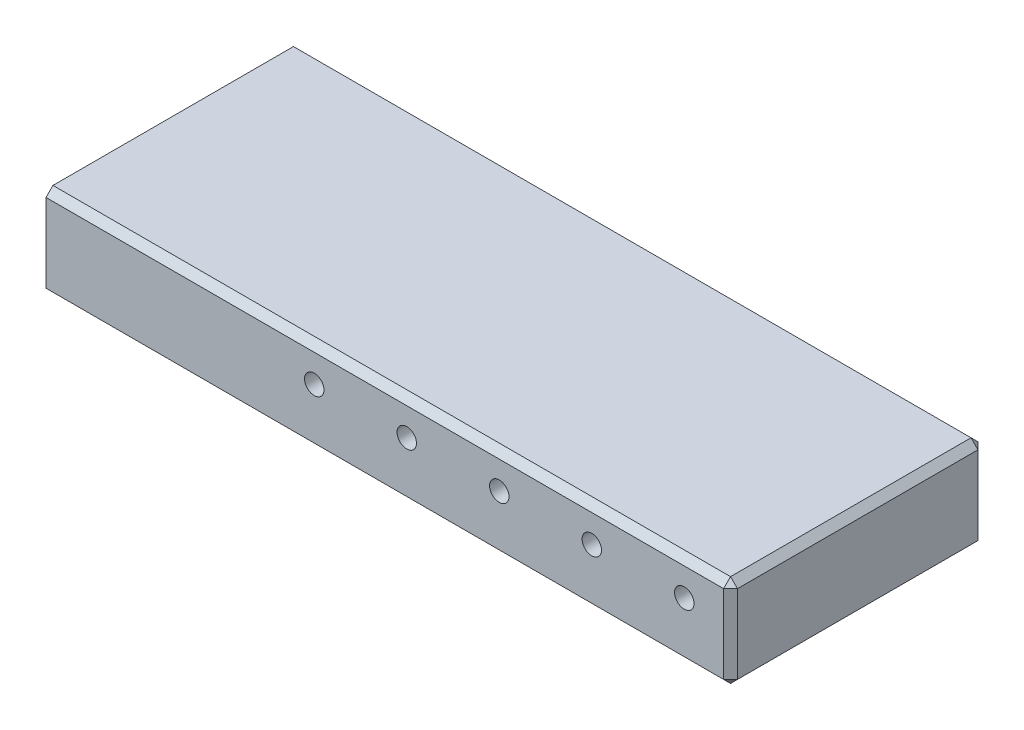
SolidWorks part; units mm, degrees
material "Alumina"
ref_plane "Front Plane" through (0, 0, 0) normal (0, 0, 1) x (1, 0, 0)
ref_plane "Top Plane" through (0, 0, 0) normal (0, 1, 0) x (1, 0, 0)
ref_plane "Right Plane" through (0, 0, 0) normal (1, 0, 0) x (0, 0, -1)
sketch "Sketch1" plane through (0, 0, 0) normal (0, 0, 1) x (1, 0, 0)
  line L5 (0, 0) -> (110, 0)
  line L7 (20, 20) -> (110, 20)
  line L8 (110, 0) -> (110, 20)
  line L10 (0, 0) -> (0, 70)
  line L11 (0, 70) -> (20, 70)
  line L12 (20, 20) -> (20, 70)
  dimension "D1" = 110
  dimension "D2" = 70
  dimension "D3" = 20
  dimension "D4" = 20
extrude "Boss-Extrude1" add sketch "Sketch1" along normal blind 55
sketch "Sketch2" plane through (0, 0, 0) normal (-1, 0, 0) x (0, 0, 1)
  line L0 (55, 0) -> (0, 0) construction
  line L1 (55, 70) -> (50, 70)
  line L2 (55, 70) -> (55, 0)
  line L3 (55, 0) -> (50, 0)
  line L4 (50, 70) -> (50, 0)
  line L6 (0, 70) -> (5, 70)
  line L7 (0, 70) -> (0, 0)
  line L8 (0, 0) -> (5, 0)
  line L9 (5, 70) -> (5, 0)
  dimension "D1" = 5
  dimension "D2" = 5
extrude "Boss-Extrude2" add sketch "Sketch2" along normal blind 5
hole_wizard "M5 Tapped Hole1" positions "Sketch3" profile "Sketch4" tap size "M5" standard "DIN"
sketch "Sketch3" plane through (0, 0, 55) normal (0, 0, 1) x (1, 0, 0)
  line L0 (110, 0) -> (110, 20) construction
  line L1 (110, 20) -> (20, 20) construction
  point P0 (100, 12.5)
  point P2 (80, 12.5)
  point P4 (60, 12.5)
  point P6 (40, 12.5)
  point P20 (20, 12.5)
  dimension "D1" = 10
  dimension "D2" = 20
  dimension "D3" = 20
  dimension "D4" = 20
  dimension "D5" = 20
  dimension "D6" = 7.5
sketch "Sketch4" plane through (100, 12.5, 55) normal (1, 0, 0) x (0, -1, 0)
  line L0 (0, 0) -> (0, 15.2618)
  line L1 (0, 15.2618) -> (2.1, 14)
  line L2 (2.1, 14) -> (2.1, 0)
  line L5 (2.1, 0) -> (0, 0)
  line L10 (0, 15.2618) -> (-2.1, 14) construction
  line L11 (0, -6.35) -> (0, 107.95) construction
  dimension "Tap Drill Dia." = 4.2
  dimension "Tap Drill Depth" = 14
  dimension "Drill Angle" = 118
cosmetic thread "Hole Thread2" parameters "D1"=10, "D2"=5
cosmetic thread "Hole Thread3" parameters "D1"=10, "D2"=5
cosmetic thread "Hole Thread4" parameters "D1"=10, "D2"=5
cosmetic thread "Hole Thread5" parameters "D1"=10, "D2"=5
cosmetic thread "Hole Thread10" parameters "D1"=10, "D2"=5
ref_plane "Plane1" through (0, 0, 27.5) normal (0, 0, 1) x (1, 0, 0)
mirror "Mirror1" about plane through (0, 0, 27.5) normal (0, 0, 1) of "M5 Tapped Hole1"
sketch "Sketch8" plane through (0, 0, 55) normal (0, 0, 1) x (1, 0, 0)
  line L0 (-5, 0) -> (110, 0) construction
  line L4 (17, 20) -> (17, 0)
  line L5 (-5, 0) -> (-5, 70) construction
  line L6 (17, 20) -> (20, 20)
  line L7 (20, 20) -> (20, 70)
  line L8 (20, 70) -> (-5, 70)
  line L9 (-5, 70) -> (-5, 0)
  line L10 (-5, 0) -> (17, 0)
  dimension "D1" = 22
extrude "Cut-Extrude1" cut sketch "Sketch8" against normal blind 126
sketch "Sketch9" plane through (17, 0, 0) normal (-1, 0, 0) x (0, 0, 1)
  line L1 (0, 20) -> (55, 20)
  line L2 (0, 20) -> (0, 0)
  line L3 (0, 0) -> (55, 0)
  line L4 (55, 20) -> (55, 0)
extrude "Boss-Extrude3" add sketch "Sketch9" along normal blind 5
chamfer "Chamfer1" distance 1.5 angle 45 8 edges at (61, 0, 0) (61, 0, 55) (61, 20, 0) (110, 0, 27.5) (110, 10, 0) (110, 20, 27.5) (110, 10, 55) (61, 20, 55)
sketch "Sketch10" plane through (12, 0, 0) normal (-1, 0, 0) x (0, 0, 1)
  line L0 (0, 18.5) -> (1.5, 20)
  line L1 (1.5, 20) -> (53.5, 20)
  line L2 (53.5, 20) -> (55, 18.5)
  line L3 (55, 18.5) -> (55, 1.5)
  line L4 (55, 1.5) -> (53.5, 0)
  line L5 (53.5, 0) -> (1.5, 0)
  line L6 (1.5, 0) -> (0, 1.5)
  line L7 (0, 1.5) -> (0, 18.5)
extrude "Boss-Extrude4" add sketch "Sketch10" along normal blind 50
hole_wizard "M6 Tapped Hole2" positions "Sketch13" profile "Sketch14" tap size "M6" standard "DIN"
sketch "Sketch13" plane through (-38, 0, 0) normal (-1, 0, 0) x (0, 0, 1)
  line L0 (0, 18.5) -> (0, 1.5) construction
  line L1 (55, 1.5) -> (55, 18.5) construction
  point P0 (15, 10)
  point P2 (40, 10)
  dimension "D1" = 15
  dimension "D2" = 15
sketch "Sketch14" plane through (-38, 10, 15) normal (0, 1, 0) x (0, 0, 1)
  line L0 (0, 0) -> (0, 25)
  line L1 (0, 25) -> (2.5, 23.4978)
  line L2 (2.5, 23.4978) -> (2.5, 0)
  line L5 (2.5, 0) -> (0, 0)
  line L10 (0, 25) -> (-2.5, 23.4978) construction
  line L11 (0, -6.35) -> (0, 107.95) construction
  dimension "Tap Drill Dia." = 5
  dimension "Tap Drill Depth" = 25
  dimension "Drill Angle" = 118
cosmetic thread "Hole Thread8" parameters "D1"=20, "D2"=6
cosmetic thread "Hole Thread9" parameters "D1"=20, "D2"=6
